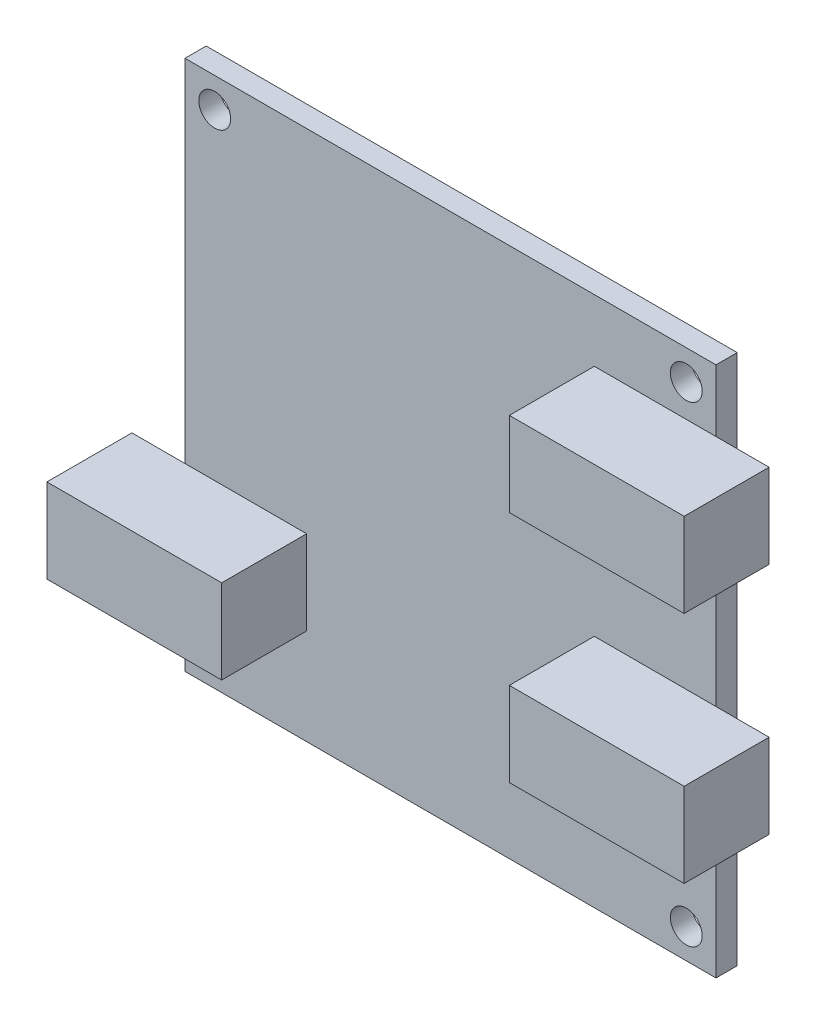
SolidWorks part; units mm, degrees
ref_plane "Ebene vorne" through (0, 0, 0) normal (1, 0, 0) x (0, 1, 0)
ref_plane "Ebene oben" through (0, 0, 0) normal (0, 0, 1) x (0, 1, 0)
ref_plane "Ebene rechts" through (0, 0, 0) normal (0, 1, 0) x (-1, 0, 0)
sketch "Skizze1" plane through (0, 0, 0) normal (0, 0, 1) x (0, 1, 0)
  line L1 (-25, -25) -> (25, -25)
  line L2 (-25, -25) -> (-25, 25)
  line L3 (-25, 25) -> (25, 25)
  line L4 (25, -25) -> (25, 25)
  line L5 (-25, -25) -> (25, 25) construction
  line L6 (-25, 25) -> (25, -25) construction
  point P0 (0, 0)
  dimension "D1" = 50
extrude "Aufsatz-Linear austragen1" add sketch "Skizze1" along normal blind 2
sketch "Skizze2" plane through (0, 0, 2) normal (0, 0, 1) x (1, 0, 0)
  line L12 (22.2, 22.2) -> (-22.2, 22.2)
  line L13 (-22.2, 22.2) -> (-22.2, -22.2)
  line L14 (-22.2, -22.2) -> (22.2, -22.2)
  line L15 (22.2, -22.2) -> (22.2, 22.2)
  line L16 (22.2, 22.2) -> (-22.2, 22.2) construction
  line L17 (-22.2, 22.2) -> (-22.2, -22.2) construction
  line L18 (-22.2, -22.2) -> (22.2, -22.2) construction
  line L19 (22.2, -22.2) -> (22.2, 22.2) construction
  circle A0 centre (22.2, 22.2) radius 1.5
  circle A1 centre (22.2, -22.2) radius 1.5
  circle A2 centre (-22.2, -22.2) radius 1.5
  circle A3 centre (-22.2, 22.2) radius 1.5
  dimension "D2" = 3
  dimension "D1" = 2.8
extrude "Schnitt-Linear austragen1" cut sketch "Skizze2" against normal blind 2
sketch "Skizze3" plane through (0, 0, 2) normal (0, 0, 1) x (1, 0, 0)
  line L0 (25, -25) -> (25, 25) construction
  line L1 (-30, -8.0457) -> (-13.5436, -8.0457)
  line L2 (-30, -8.0457) -> (-30, -15.9736)
  line L3 (-30, -15.9736) -> (-13.5436, -15.9736)
  line L4 (-13.5436, -8.0457) -> (-13.5436, -15.9736)
  line L5 (13.5436, 19.1526) -> (30, 19.1526)
  line L6 (13.5436, 19.1526) -> (13.5436, 11.2247)
  line L7 (13.5436, 11.2247) -> (30, 11.2247)
  line L8 (30, 19.1526) -> (30, 11.2247)
  line L9 (13.5436, -2.865) -> (30, -2.865)
  line L10 (13.5436, -2.865) -> (13.5436, -10.793)
  line L11 (13.5436, -10.793) -> (30, -10.793)
  line L12 (30, -2.865) -> (30, -10.793)
  line L13 (-25, 25) -> (-25, -25) construction
  dimension "D1" = 5
  dimension "D2" = 5
extrude "Aufsatz-Linear austragen2" add sketch "Skizze3" along normal blind 8 separate body
